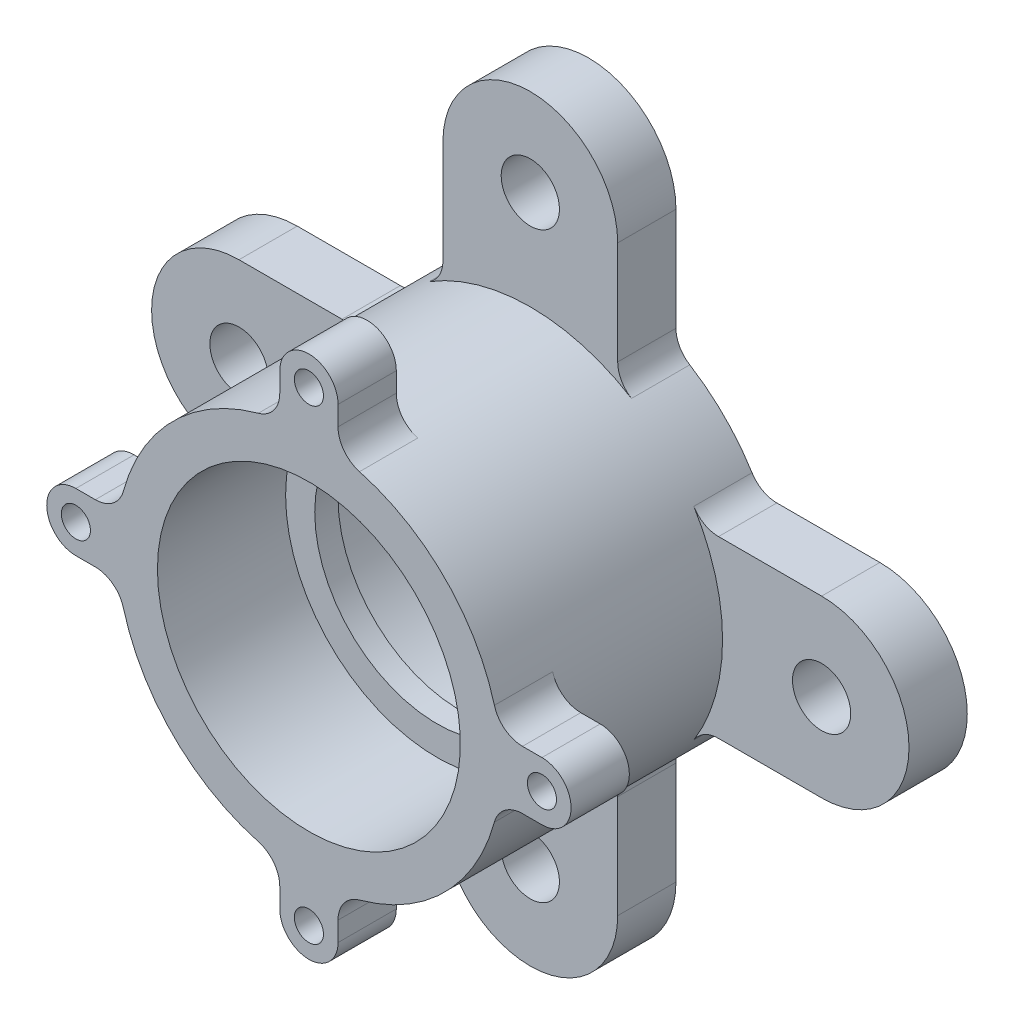
SolidWorks part; units mm, degrees
ref_plane "Front Plane" through (0, 0, 0) normal (1, 0, 0) x (0, 1, 0)
ref_plane "Top Plane" through (0, 0, 0) normal (0, 0, 1) x (0, 1, 0)
ref_plane "Right Plane" through (0, 0, 0) normal (0, 1, 0) x (-1, 0, 0)
sketch "Sketch2" plane through (0, 0, 0) normal (0, 1, 0) x (-1, 0, 0)
  line L0 (26, 0) -> (26, 48)
  line L1 (0, 0) -> (33, 0)
  line L2 (0, 0) -> (0, 48) construction
  line L3 (0, 48) -> (33, 48)
  line L4 (33, 0) -> (33, 48)
  line L6 (26, 22) -> (21, 22)
  line L7 (26, 22) -> (26, 26)
  line L8 (26, 26) -> (21, 26)
  line L9 (21, 22) -> (21, 26)
  dimension "D1" = 33
  dimension "D2" = 48
  dimension "D4" = 22
  dimension "D5" = 4
  dimension "D6" = 5
  dimension "D3" = 7
revolve "Revolve1" add sketch "Sketch2" angle 360 about L2
sketch "Sketch3" plane through (0, 0, 0) normal (0, 0, -1) x (1, 0, 0)
  line L0 (0, 0) -> (0, 50) construction
  line L1 (-15, 50) -> (-15, 29.3939)
  line L2 (15, 50) -> (15, 29.3939)
  line L3 (15, 50) -> (-15, 50)
  line L4 (-15, 29.3939) -> (15, 29.3939)
  line L5 (29.3939, 15) -> (29.3939, -15)
  line L6 (50, -15) -> (29.3939, -15)
  line L7 (50, -15) -> (50, 15)
  line L8 (50, 15) -> (29.3939, 15)
  line L9 (15, -29.3939) -> (-15, -29.3939)
  line L10 (-15, -50) -> (-15, -29.3939)
  line L11 (-15, -50) -> (15, -50)
  line L12 (15, -50) -> (15, -29.3939)
  line L13 (-29.3939, -15) -> (-29.3939, 15)
  line L14 (-50, 15) -> (-29.3939, 15)
  line L15 (-50, 15) -> (-50, -15)
  line L16 (-50, -15) -> (-29.3939, -15)
  circle A0 centre (0, 50) radius 5
  circle A1 centre (0, 50) radius 15
  circle A2 centre (0, 0) radius 33 construction
  circle A3 centre (50, 0) radius 15
  circle A4 centre (50, 0) radius 5
  circle A5 centre (0, -50) radius 15
  circle A6 centre (0, -50) radius 5
  circle A7 centre (-50, 0) radius 15
  circle A8 centre (-50, 0) radius 5
  point P35 (0, 0)
  circle M8 centre (0, 0) radius 33
  dimension "D2" = 10
  dimension "D3" = 30
  dimension "D1" = 50
  dimension "D4" = 4
extrude "Boss-Extrude1" add sketch "Sketch3" against normal blind 10 contours A8 L15 A7 | A8 L15 A7 | A7 L16 L14 M8 | L3 A1 A0 | A1 L0 A0 L3 | L0 A1 L3 A0 | L0 L2 A1 M8 | L0 A1 L1 M8 | A4 L7 A3 | A3 L8 L6 M8 | A4 L7 A3 | A5 L12 L10 M8 | A6 L11 A5 | A6 L11 A5
sketch "Sketch4" plane through (0, 0, 48) normal (0, 0, 1) x (1, 0, 0)
  line L0 (0, 0) -> (0, 40) construction
  line L1 (-5, 40) -> (-5, 29.9879)
  line L2 (-5, 29.9879) -> (5, 29.9879)
  line L3 (5, 29.9879) -> (5, 40)
  line L4 (5, 40) -> (-5, 40)
  line L5 (29.9879, -5) -> (40, -5)
  line L6 (40, 5) -> (29.9879, 5)
  line L7 (29.9879, 5) -> (29.9879, -5)
  line L8 (-5, -29.9879) -> (-5, -40)
  line L9 (5, -40) -> (5, -29.9879)
  line L10 (5, -29.9879) -> (-5, -29.9879)
  line L11 (-29.9879, 5) -> (-40, 5)
  line L12 (-40, -5) -> (-29.9879, -5)
  line L13 (-29.9879, -5) -> (-29.9879, 5)
  circle A0 centre (0, 40) radius 2.5
  circle A1 centre (0, 40) radius 5
  circle A2 centre (40, 0) radius 5
  circle A3 centre (40, 0) radius 2.5
  circle A4 centre (0, -40) radius 5
  circle A5 centre (0, -40) radius 2.5
  circle A6 centre (-40, 0) radius 5
  circle A7 centre (-40, 0) radius 2.5
  point P33 (0, 0)
  circle M8 centre (0, 0) radius 33
  dimension "D2" = 5
  dimension "D3" = 10
  dimension "D1" = 40
  dimension "D4" = 4
extrude "Boss-Extrude2" add sketch "Sketch4" against normal blind 10 contours A4 A5 | A4 L9 L8 M8 | A2 L6 L5 M8 | A1 L0 A0 L4 | L4 A1 A0 | L0 L3 A1 M8 | L0 A1 L1 M8 | L0 A1 L4 A0 | A6 L12 L11 M8 | A6 A7 | A3
fillet "Fillet1" radius 5 16 edges at (-15, 29.3939, 5) (-29.3939, 15, 5) (-29.3939, -15, 5) (-15, -29.3939, 5) (15, -29.3939, 5) (29.3939, -15, 5) (15, 29.3939, 5) (29.3939, 15, 5) (-32.619, 5, 43) (-5, 32.619, 43) (5, 32.619, 43) (32.619, -5, 43) (32.619, 5, 43) (5, -32.619, 43) (-5, -32.619, 43) (-32.619, -5, 43)
